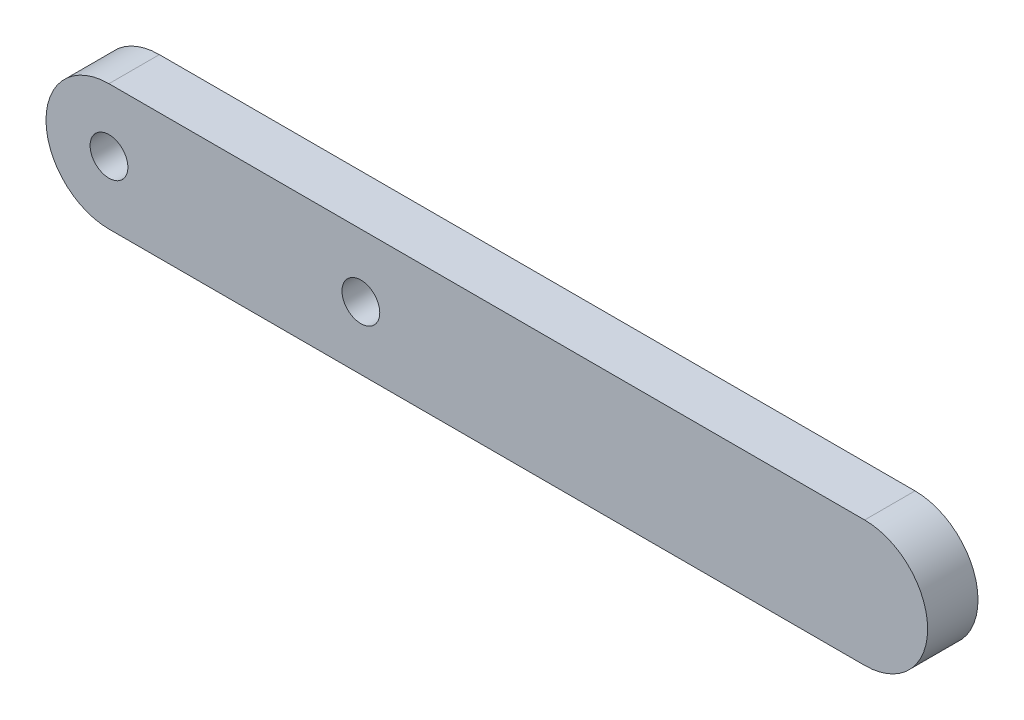
SolidWorks part; units mm, degrees
ref_plane "Plan de face" through (0, 0, 0) normal (0, 0, 1) x (1, 0, 0)
ref_plane "Plan de dessus" through (0, 0, 0) normal (0, 1, 0) x (1, 0, 0)
ref_plane "Plan de droite" through (0, 0, 0) normal (1, 0, 0) x (0, 0, -1)
sketch "Esquisse1" plane through (0, 0, 0) normal (0, 0, 1) x (1, 0, 0)
  line L0 (-30, 0) -> (30, 0) construction
  line L1 (-30, 5) -> (30, 5)
  line L2 (-30, -5) -> (30, -5)
  arc A0 (-30, 5) -> (-30, -5) centre (-30, 0) ccw
  arc A1 (30, -5) -> (30, 5) centre (30, 0) ccw
  circle A2 centre (-30, 0) radius 1.5
  circle A4 centre (-10, 0) radius 1.5
  point P2 (0, 0)
  dimension "D1" = 3
  dimension "D2" = 10
  dimension "D4" = 20
  dimension "D5" = 3
  dimension "D3" = 60
extrude "Boss.-Extru.1" add sketch "Esquisse1" along normal blind 4
